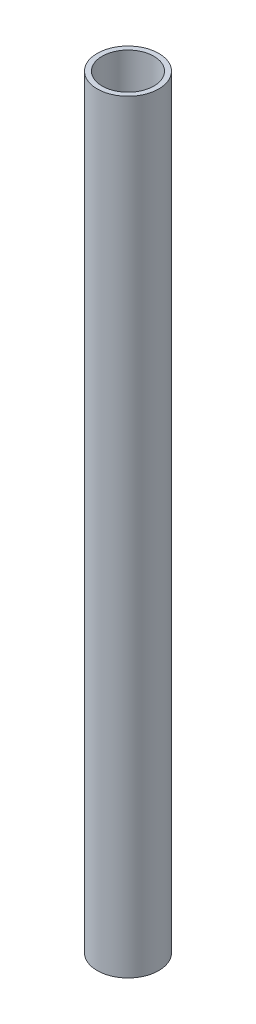
SolidWorks part; units mm, degrees
ref_plane "Alzado" through (0, 0, 0) normal (0, 0, 1) x (1, 0, 0)
ref_plane "Planta" through (0, 0, 0) normal (0, 1, 0) x (1, 0, 0)
ref_plane "Vista lateral" through (0, 0, 0) normal (1, 0, 0) x (0, 0, -1)
sketch "Croquis1" plane through (0, 0, 0) normal (0, 1, 0) x (1, 0, 0)
  circle A0 centre (0, 0) radius 12.5
  circle A1 centre (0, 0) radius 10.5
  dimension "D1" = 25
  dimension "D2" = 2
extrude "Saliente-Extruir1" add sketch "Croquis1" along normal blind 310
